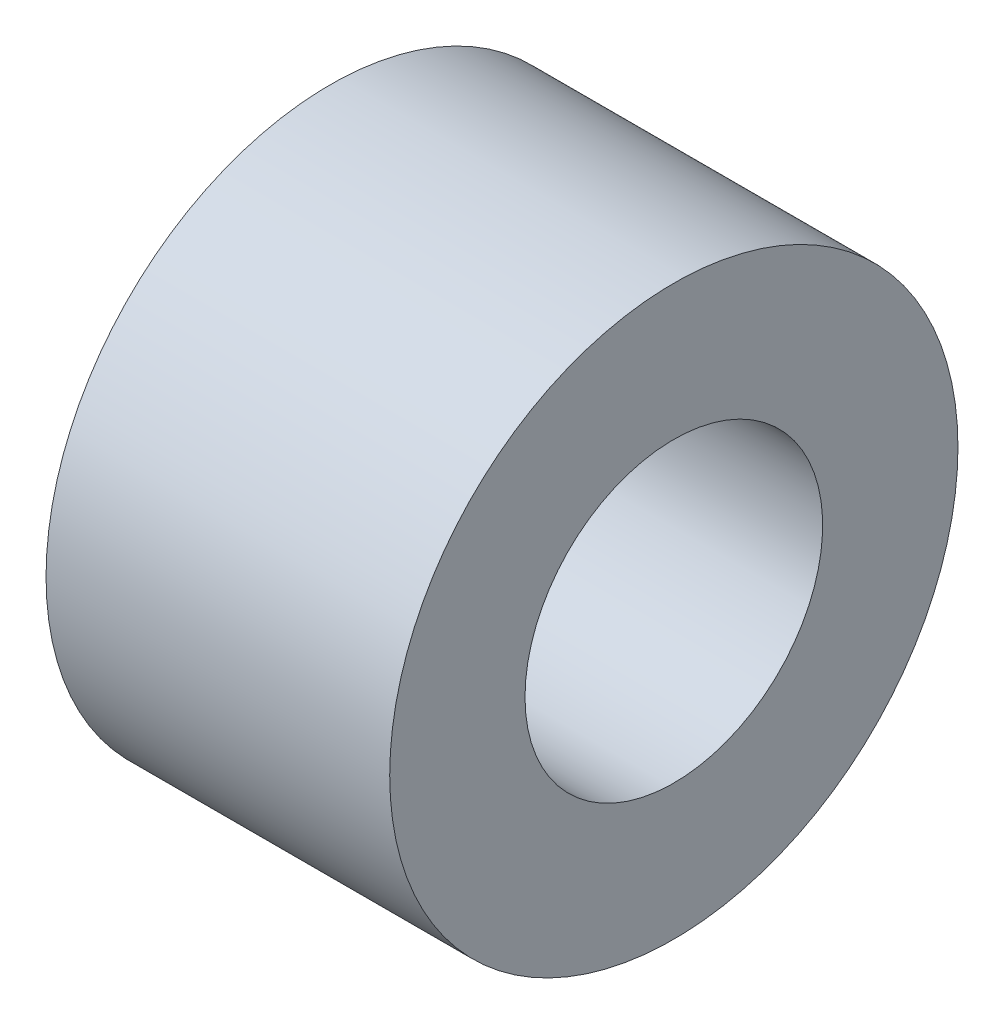
SolidWorks part; units mm, degrees
ref_plane "Front Plane" through (0, 0, 0) normal (0, 0, 1) x (1, 0, 0)
ref_plane "Top Plane" through (0, 0, 0) normal (0, 1, 0) x (1, 0, 0)
ref_plane "Right Plane" through (0, 0, 0) normal (1, 0, 0) x (0, 0, -1)
sketch "Sketch1" plane through (0, 0, 0) normal (0, 0, 1) x (1, 0, 0)
  line L0 (-32.3193, 0) -> (32.3193, 0) construction
  line L1 (0, -35.3683) -> (0, 35.3683) construction
  line L2 (-12.7, 21) -> (12.7, 21)
  line L3 (-12.7, 11) -> (12.7, 11)
  line L4 (-12.7, 21) -> (-12.7, 11)
  line L5 (12.7, 21) -> (12.7, 11)
  point P7 (0, 21)
  dimension "D1" = 42
  dimension "D2" = 22
  dimension "D3" = 25.4
revolve "Revolve1" add sketch "Sketch1" angle 360 about L0
